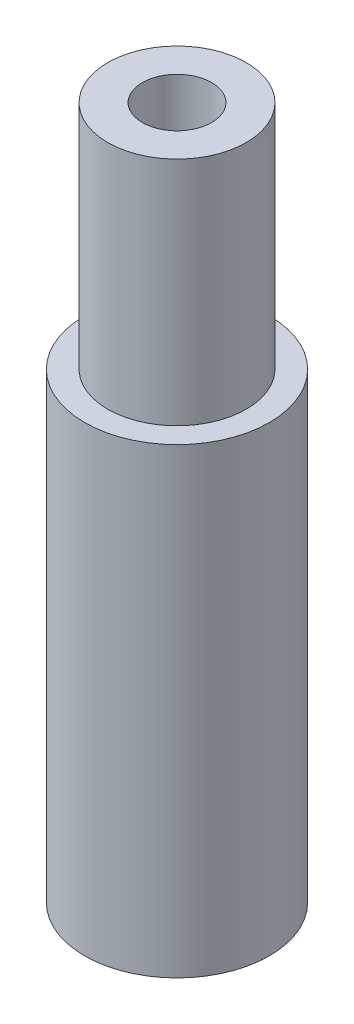
SolidWorks part; units mm, degrees
material "黄铜"
ref_plane "前视基准面" through (0, 0, 0) normal (0, 0, 1) x (1, 0, 0)
ref_plane "上视基准面" through (0, 0, 0) normal (0, 1, 0) x (1, 0, 0)
ref_plane "右视基准面" through (0, 0, 0) normal (1, 0, 0) x (0, 0, -1)
sketch "草图1" plane through (0, 0, 0) normal (0, 1, 0) x (1, 0, 0)
  circle A0 centre (0, 0) radius 4
  dimension "D1" = 8
extrude "凸台-拉伸1" add sketch "草图1" along normal blind 20
sketch "草图2" plane through (0, 20, 0) normal (0, 1, 0) x (1, 0, 0)
  circle A0 centre (0, 0) radius 3
extrude "凸台-拉伸2" add sketch "草图2" along normal blind 10
sketch "草图3" plane through (0, 30, 0) normal (0, 1, 0) x (1, 0, 0)
  circle A0 centre (0, 0) radius 1.5
extrude "切除-拉伸1" cut sketch "草图3" against normal up to surface (10 mm away) up to face at (0, 20, 3)
